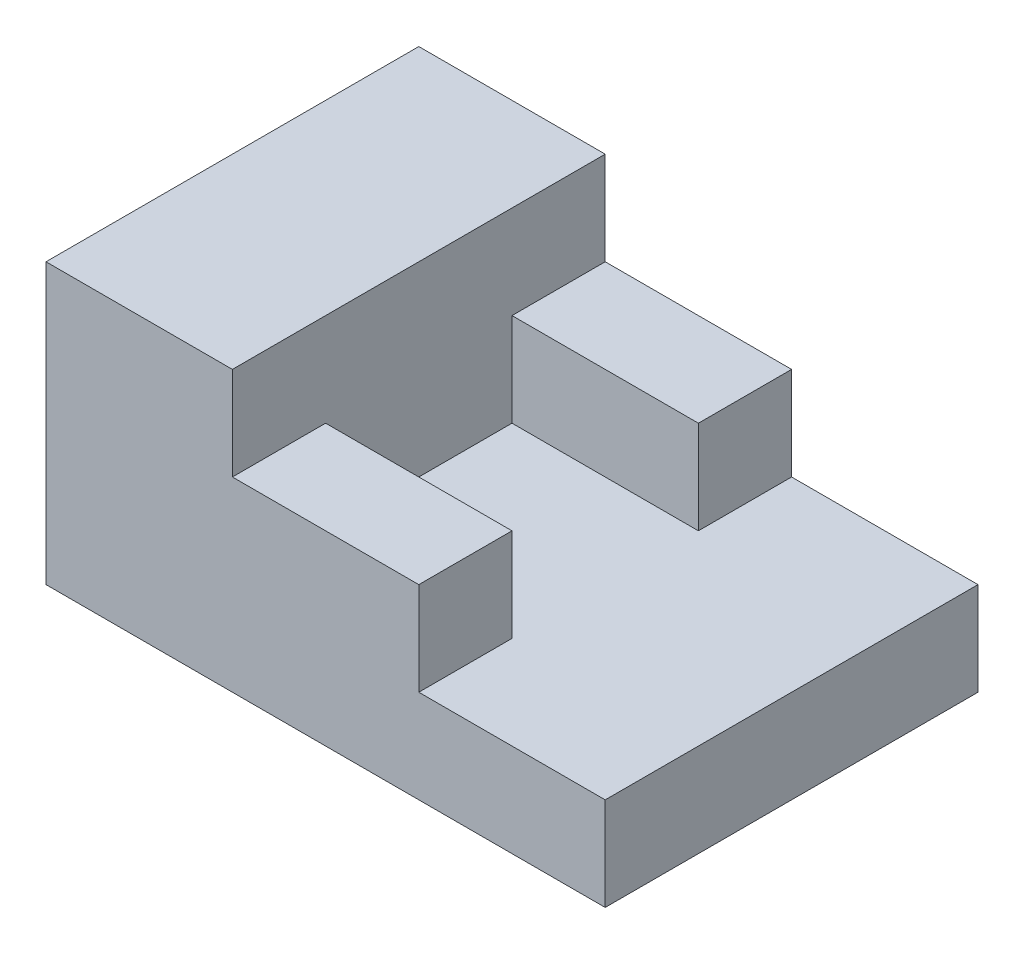
SolidWorks part; units mm, degrees
ref_plane "Front Plane" through (0, 0, 0) normal (0, 0, 1) x (1, 0, 0)
ref_plane "Top Plane" through (0, 0, 0) normal (0, 1, 0) x (1, 0, 0)
ref_plane "Right Plane" through (0, 0, 0) normal (1, 0, 0) x (0, 0, -1)
sketch "Sketch1" plane through (0, 0, 0) normal (0, 0, 1) x (1, 0, 0)
  line L0 (-37.284, 15.679) -> (-37.284, -14.321)
  line L1 (-37.284, -14.321) -> (22.716, -14.321)
  line L2 (22.716, -14.321) -> (22.716, -4.321)
  line L3 (22.716, -4.321) -> (2.716, -4.321)
  line L4 (2.716, -4.321) -> (2.716, 5.679)
  line L5 (2.716, 5.679) -> (-17.284, 5.679)
  line L6 (-17.284, 5.679) -> (-17.284, 15.679)
  line L7 (-17.284, 15.679) -> (-37.284, 15.679)
  dimension "D1" = 30
  dimension "D2" = 60
  dimension "D3" = 20
  dimension "D4" = 20
  dimension "D5" = 10
  dimension "D6" = 10
  dimension "D7" = 10
extrude "Boss-Extrude1" add sketch "Sketch1" along normal blind 40
sketch "Sketch2" plane through (0, 5.679, 0) normal (0, 1, 0) x (1, 0, 0)
  line L0 (-17.284, -30) -> (-17.284, -10)
  line L1 (-17.284, -40) -> (-17.284, 0) construction
  line L3 (2.716, 0) -> (-17.284, 0) construction
  line L4 (-17.284, -10) -> (2.716, -10)
  line L5 (2.716, -40) -> (2.716, 0) construction
  line L6 (2.716, -10) -> (2.716, -30)
  line L7 (2.716, -30) -> (-17.284, -30)
  point P5 (-17.284, -20)
  dimension "D1" = 20
  dimension "D2" = 10
extrude "Cut-Extrude1" cut sketch "Sketch2" against normal blind 10 contours L7 L0 L4 L6
